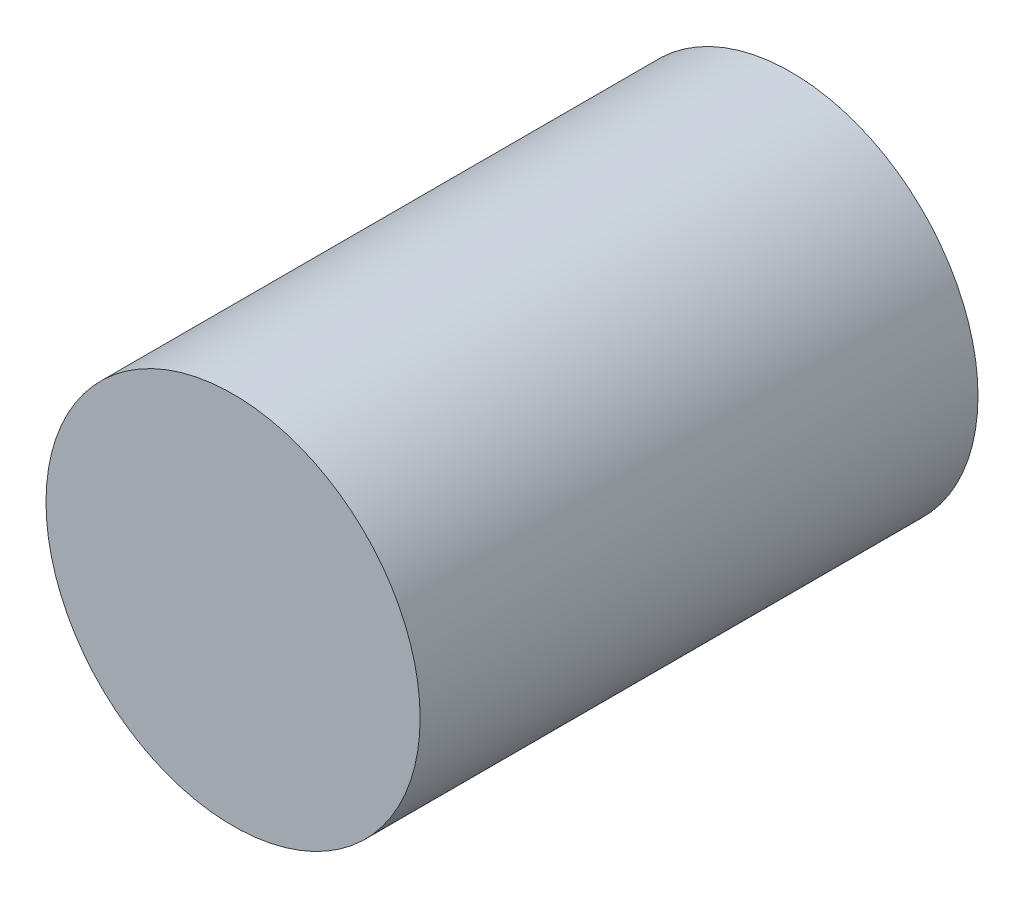
SolidWorks part; units mm, degrees
ref_plane "Front Plane" through (0, 0, 0) normal (0, 0, 1) x (1, 0, 0)
ref_plane "Top Plane" through (0, 0, 0) normal (0, 1, 0) x (1, 0, 0)
ref_plane "Right Plane" through (0, 0, 0) normal (1, 0, 0) x (0, 0, -1)
sketch "Sketch1" plane through (0, 0, 0) normal (0, 0, 1) x (1, 0, 0)
  circle A0 centre (0, 0) radius 18.375
  dimension "D1" = 36.75
extrude "Boss-Extrude1" add sketch "Sketch1" along normal blind 54.8
